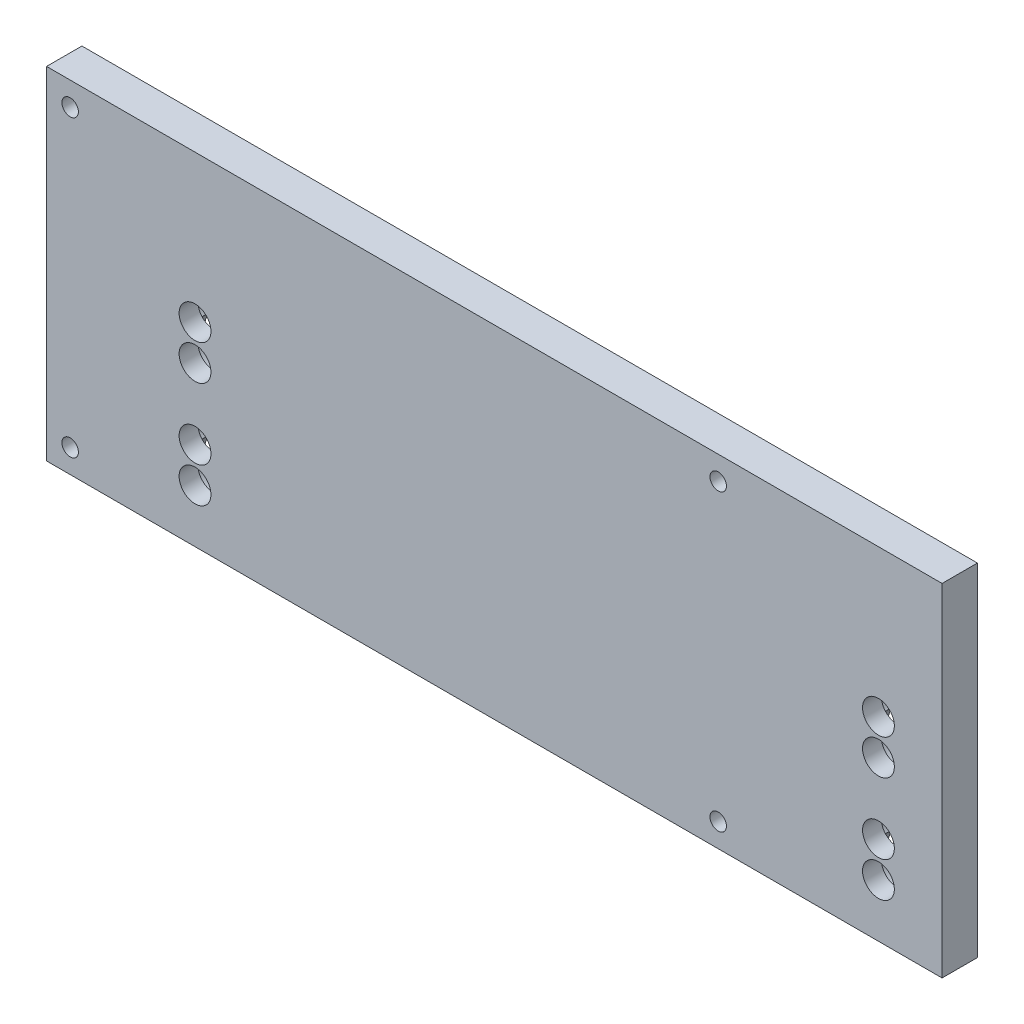
SolidWorks part; units mm, degrees
ref_plane "Front Plane" through (0, 0, 0) normal (0, 0, 1) x (1, 0, 0)
ref_plane "Top Plane" through (0, 0, 0) normal (0, 1, 0) x (1, 0, 0)
ref_plane "Right Plane" through (0, 0, 0) normal (1, 0, 0) x (0, 0, -1)
ref_plane "Ebene1" through (0, 0, 0) normal (0, 0, -1) x (-1, 0, 0)
sketch "Skizze1" plane through (0, 0, 0) normal (0, 0, -1) x (-1, 0, 0)
  line L0 (0, 0) -> (-380, 0)
  line L1 (-380, 0) -> (-380, -145)
  line L2 (-380, -145) -> (0, -145)
  line L3 (0, -145) -> (0, 0)
extrude "Aufsatz-Linear austragen1" add sketch "Skizze1" against normal blind 15
hole_wizard "Ø7.0 (7) Durchmesser Bohrung1" positions "Skizze3" profile "Skizze2" hole size "Ø7.0" standard "ANSI Metrisch"
sketch "Skizze3" plane through (0, 0, 0) normal (0, 0, -1) x (-1, 0, 0)
  point P0 (-10, -135)
  point P1 (-10, -10)
  point P2 (-285, -10)
  point P3 (-285, -135)
sketch "Skizze2" plane through (10, -135, 0) normal (1, 0, 0) x (0, 1, 0)
  line L0 (0, 0) -> (0, 15)
  line L1 (0, 15) -> (3.5, 15)
  line L2 (3.5, 15) -> (3.5, 0)
  line L5 (3.5, 0) -> (0, 0)
  line L11 (0, -6.35) -> (0, 107.95) construction
  dimension "Bohrerdurchmesser" = 7
  dimension "Bohrungstiefe" = 15
hole_wizard "Stirnsenkung für M12 Sechskantschraube mit Schaft1" positions "Skizze5" profile "Skizze4" counterbore size "M12" standard "ANSI Metrisch"
sketch "Skizze5" plane through (0, 0, 0) normal (0, 0, -1) x (-1, 0, 0)
  line L0 (-63, -62.5) -> (-63, -107.5) construction
  line L3 (-353, -107.5) -> (-353, -62.5) construction
  line L6 (-63, -107.5) -> (-353, -107.5) construction
  line L9 (-63, -62.5) -> (-353, -62.5) construction
  line L12 (-380, -145) -> (0, -145) construction
  line L13 (-380, 0) -> (-380, -145) construction
  point P0 (-63, -62.5)
  point P1 (-63, -107.5)
  point P2 (-353, -107.5)
  point P3 (-353, -62.5)
  dimension "D1" = 45
  dimension "D2" = 290
  dimension "D3" = 37.5
  dimension "D4" = 27
sketch "Skizze4" plane through (63, -62.5, 0) normal (1, 0, 0) x (0, 1, 0)
  line L0 (0, 0) -> (0, 15)
  line L1 (0, 15) -> (6.75, 15)
  line L3 (6.75, 15) -> (6.75, 7)
  line L4 (6.75, 7) -> (11, 7)
  line L5 (11, 7) -> (11, 0)
  line L7 (11, 0) -> (0, 0)
  line L11 (0, -6.35) -> (0, 107.95) construction
  dimension "Bohrerdurchmesser" = 13.5
  dimension "Bohrungstiefe" = 15
  dimension "Senkdurchmesser2" = 22
  dimension "Senktiefe2" = 7
pattern_linear "Lineares Muster1" count 2 spacing 15 along (0, -1, 0) of "Stirnsenkung für M12 Sechskantschraube mit Schaft1"
